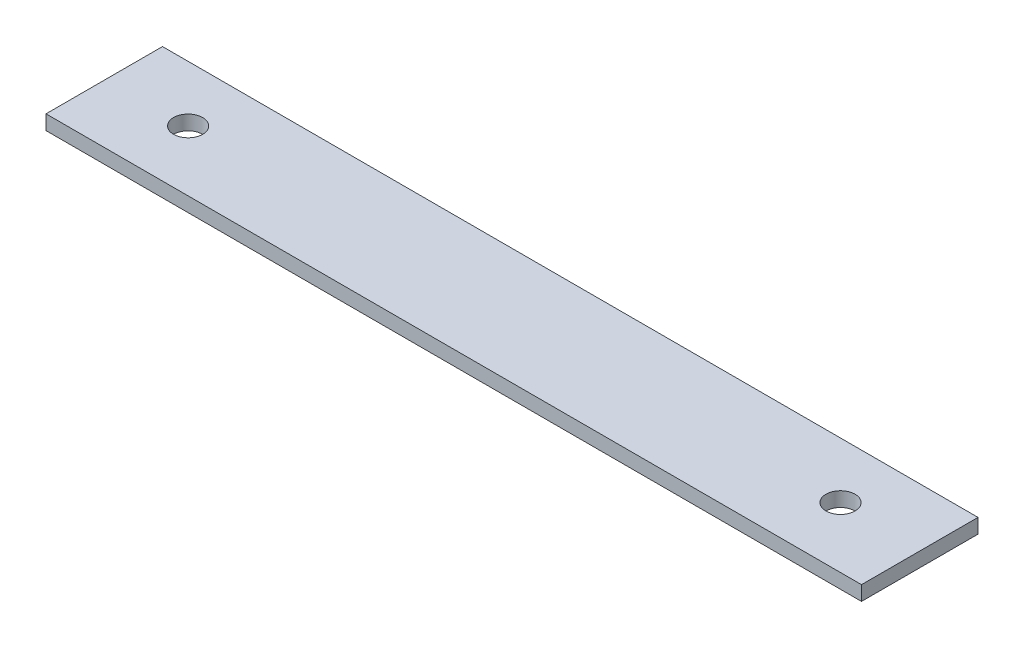
SolidWorks part; units mm, degrees
ref_plane "Front Plane" through (0, 0, 0) normal (0, 0, 1) x (1, 0, 0)
ref_plane "Top Plane" through (0, 0, 0) normal (0, 1, 0) x (1, 0, 0)
ref_plane "Right Plane" through (0, 0, 0) normal (1, 0, 0) x (0, 0, -1)
sketch "Sketch1" plane through (0, 0, 0) normal (0, 1, 0) x (1, 0, 0)
  line L1 (-103.6529, 23.958) -> (74.1471, 23.958)
  line L2 (-103.6529, 23.958) -> (-103.6529, -1.442)
  line L3 (-103.6529, -1.442) -> (74.1471, -1.442)
  line L4 (74.1471, 23.958) -> (74.1471, -1.442)
  circle A0 centre (56.3671, 11.7612) radius 3.175
  circle A1 centre (-85.8729, 11.7612) radius 3.175
  dimension "D5" = 6.35
  dimension "D6" = 6.35
  dimension "D1" = 177.8
  dimension "D2" = 25.4
  dimension "D3" = 17.78
  dimension "D4" = 17.78
extrude "Boss-Extrude1" add sketch "Sketch1" along normal blind 3.175
